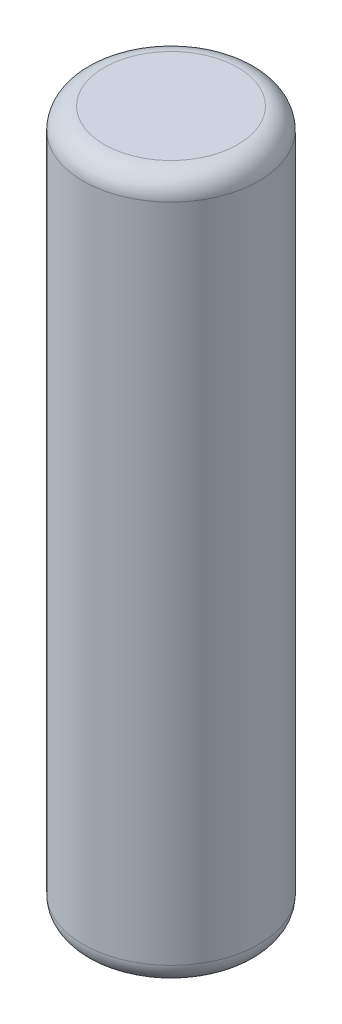
SolidWorks part; units mm, degrees
ref_plane "Front Plane" through (0, 0, 0) normal (0, 0, 1) x (1, 0, 0)
ref_plane "Top Plane" through (0, 0, 0) normal (0, 1, 0) x (1, 0, 0)
ref_plane "Right Plane" through (0, 0, 0) normal (1, 0, 0) x (0, 0, -1)
sketch "Sketch1" plane through (0, 0, 0) normal (0, 1, 0) x (1, 0, 0)
  circle A0 centre (0, 0) radius 1.25
  dimension "D1" = 2.5
extrude "Boss-Extrude1" add sketch "Sketch1" along normal blind 10
fillet "Fillet1" radius 0.3 2 edges at (0, 0, 1.25) (0, 10, 1.25)
